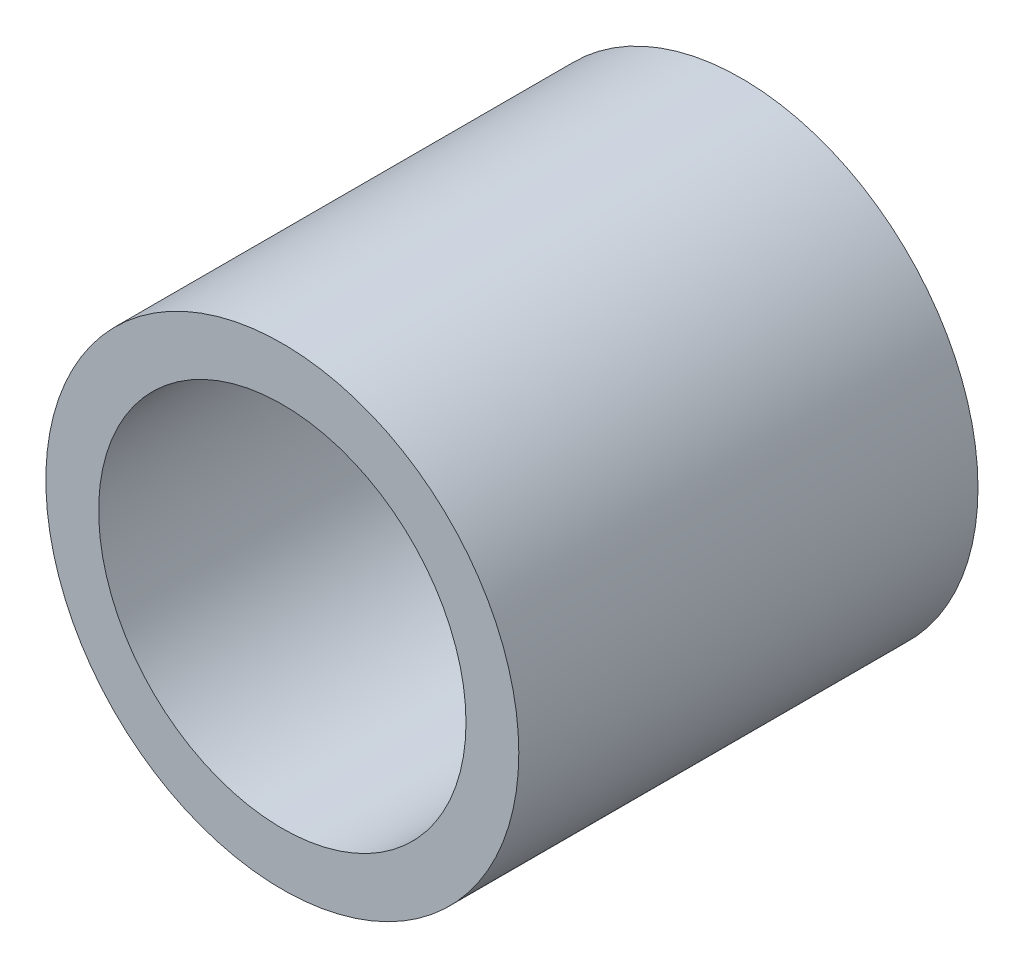
SolidWorks part; units mm, degrees
material "1060 Alloy"
ref_plane "Front Plane" through (0, 0, 0) normal (0, 0, 1) x (1, 0, 0)
ref_plane "Top Plane" through (0, 0, 0) normal (0, 1, 0) x (1, 0, 0)
ref_plane "Right Plane" through (0, 0, 0) normal (1, 0, 0) x (0, 0, -1)
sketch "Sketch2" plane through (0, 0, 0) normal (0, 0, 1) x (1, 0, 0)
  circle A0 centre (0, 0) radius 4
  circle A1 centre (0, 0) radius 5.15
  dimension "D1" = 8
  dimension "D2" = 10.3
extrude "Boss-Extrude1" add sketch "Sketch2" along normal mid plane 10
